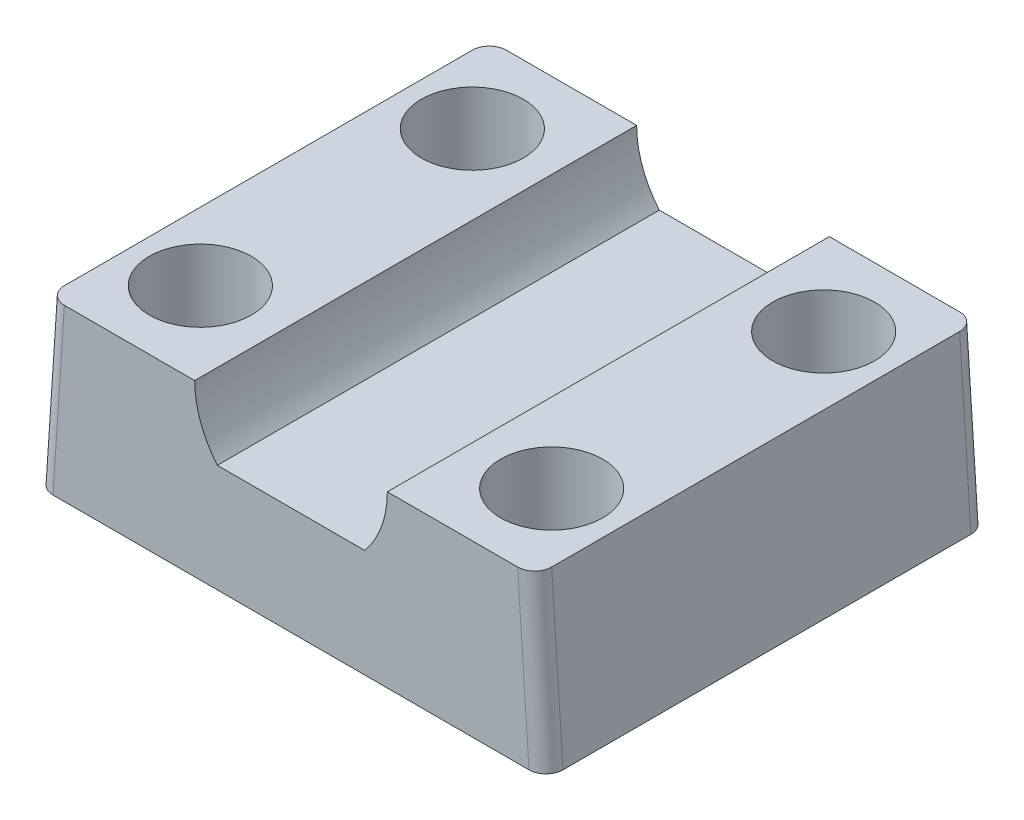
SolidWorks part; units mm, degrees
material "Acciaio inossidabile fuso"
ref_plane "Piano frontale" through (0, 0, 0) normal (0, 0, 1) x (1, 0, 0)
ref_plane "Piano superiore" through (0, 0, 0) normal (0, 1, 0) x (1, 0, 0)
ref_plane "Piano destro" through (0, 0, 0) normal (1, 0, 0) x (0, 0, -1)
sketch "Schizzo1" plane through (0, 0, 0) normal (0, 0, 1) x (1, 0, 0)
  line L0 (-21.5, 15) -> (-22.5, 0)
  line L1 (-22.5, 0) -> (22.5, 0)
  line L2 (22.5, 0) -> (21.5, 15)
  line L3 (21.5, 15) -> (8.5, 15)
  line L4 (-21.5, 15) -> (-8.5, 15)
  line L5 (-6.5, 9.5228) -> (6.5, 9.5228)
  line L6 (0, 15) -> (0, 0) construction
  arc A0 (6.5, 9.5228) -> (8.5, 15) centre (0, 15) ccw
  arc A1 (-8.5, 15) -> (-6.5, 9.5228) centre (0, 15) ccw
  point P2 (0, 0)
  point P9 (5.17, 11.8672)
  dimension "D2" = 17
  dimension "D1" = 45
  dimension "D3" = 43
  dimension "D4" = 15
  dimension "D5" = 13
extrude "Estrusione-Estrusione1" add sketch "Schizzo1" along normal blind 39
sketch "Schizzo2" plane through (0, 0, 0) normal (0, -1, 0) x (-1, 0, 0)
  line L0 (-15.5, -7.5) -> (-15.5, -31.5) construction
  line L1 (-15.5, -31.5) -> (15.5, -31.5) construction
  line L2 (15.5, -31.5) -> (15.5, -7.5) construction
  line L3 (15.5, -7.5) -> (-15.5, -7.5) construction
  point P0 (-15.5, -31.5)
  point P2 (15.5, -31.5)
  point P4 (15.5, -7.5)
  point P6 (-15.5, -7.5)
  dimension "D1" = 31
  dimension "D2" = 24
  dimension "D3" = 15.5
  dimension "D4" = 7.5
hole_wizard "Foro per Vite M8-1" positions "Schizzo2" profile "Schizzo3" hole size "M8" standard "ISO"
sketch "Schizzo3" plane through (15.5, 0, 31.5) normal (1, 0, 0) x (0, 0, -1)
  line L0 (0, 0) -> (0, 32.7039)
  line L1 (0, 32.7039) -> (4.5, 30)
  line L2 (4.5, 30) -> (4.5, 0)
  line L5 (4.5, 0) -> (0, 0)
  line L10 (0, 32.7039) -> (-4.5, 30) construction
  line L11 (0, -6.35) -> (0, 107.95) construction
  dimension "Hole Dia." = 9
  dimension "Hole Depth" = 30
  dimension "Drill Angle" = 118
fillet "Raccordo1" radius 1.5 4 edges at (-22, 7.5, 39) (22, 7.5, 39) (22, 7.5, 0) (-22, 7.5, 0)
